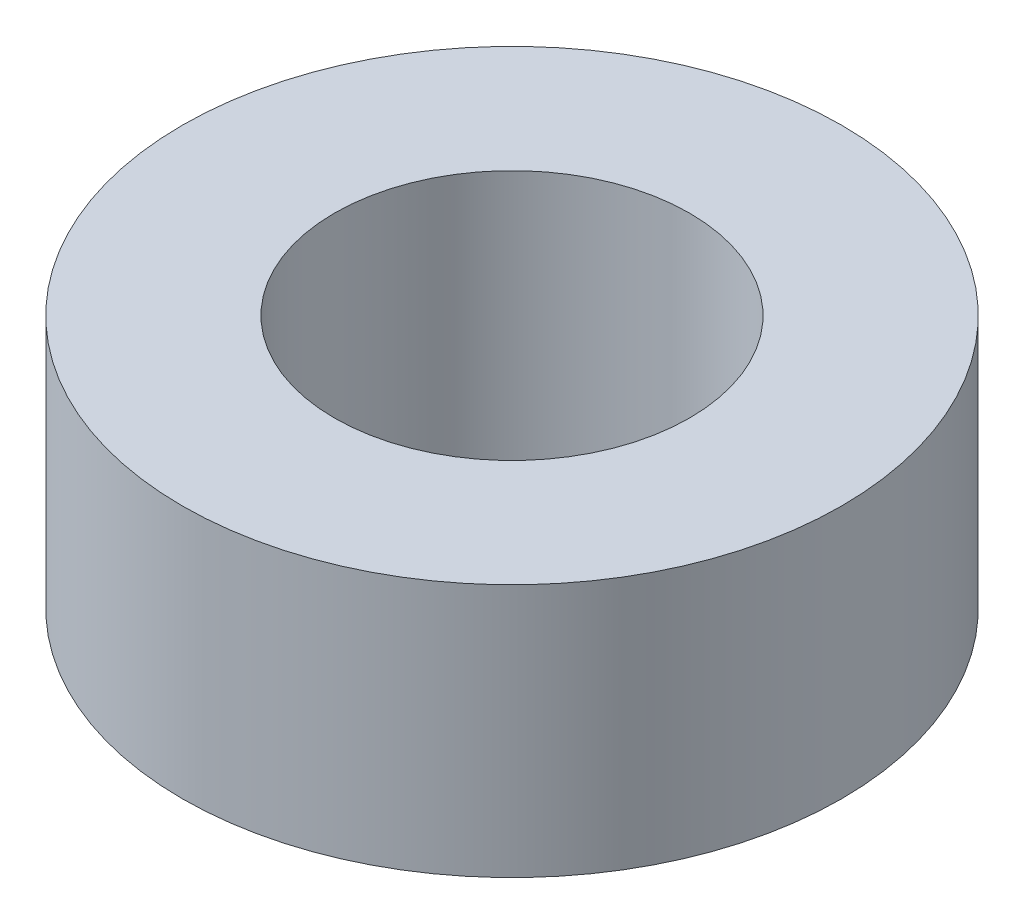
SolidWorks part; units mm, degrees
ref_plane "Front Plane" through (0, 0, 0) normal (0, 0, 1) x (1, 0, 0)
ref_plane "Top Plane" through (0, 0, 0) normal (0, 1, 0) x (1, 0, 0)
ref_plane "Right Plane" through (0, 0, 0) normal (1, 0, 0) x (0, 0, -1)
sketch "Sketch1" plane through (0, 0, 0) normal (0, 1, 0) x (1, 0, 0)
  circle A0 centre (0, 0) radius 3.5
  circle A1 centre (0, 0) radius 6.5
  dimension "D1" = 7
  dimension "D2" = 13
extrude "Boss-Extrude1" add sketch "Sketch1" along normal blind 5
sketch "Sketch2" plane through (0, 0, 0) normal (1, 0, 0) x (0, 0, -1)
  line L0 (-6.5, 0) -> (6.5, 0) construction
  line L1 (-6.5, 5) -> (-6.5, 0) construction
  line L2 (0, 5.6053) -> (0, -0.5751) construction
  circle A0 centre (-5, 4) radius 0.5
  circle A1 centre (-5, 2.5) radius 0.5
  circle A2 centre (-5, 1) radius 0.5
  dimension "D1" = 1
  dimension "D2" = 1
  dimension "D3" = 1.5
  dimension "D4" = 1.5
  dimension "D5" = 1.5
revolve "Cut-Revolve1" cut sketch "Sketch2" angle 360 about L2
